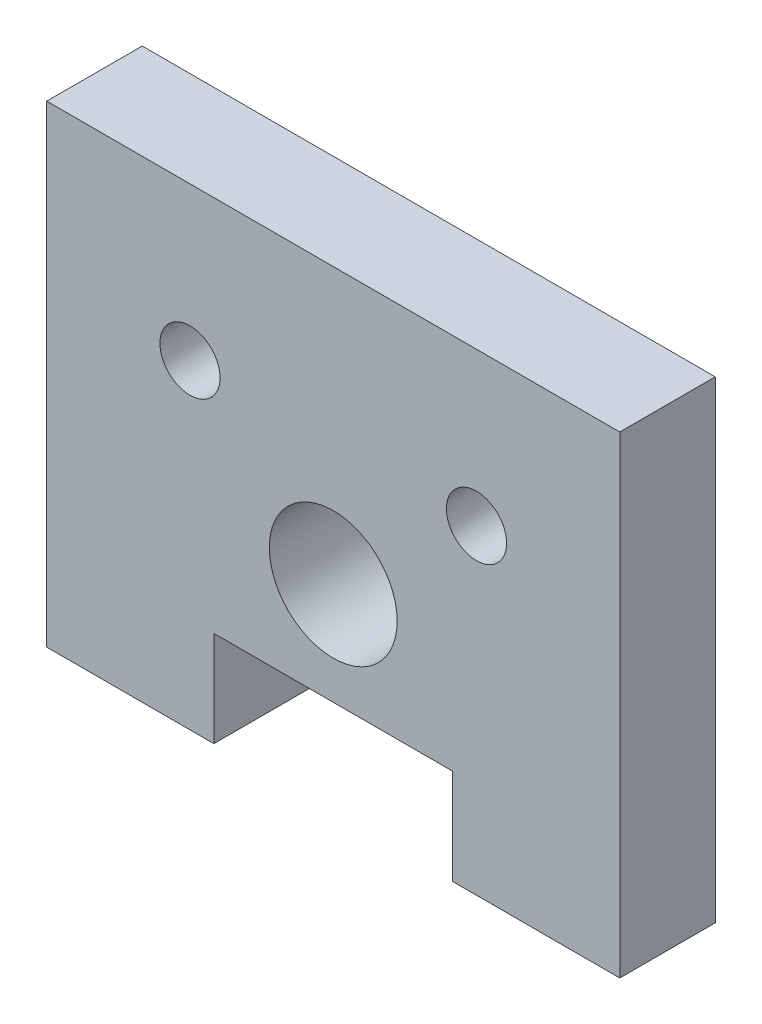
SolidWorks part; units mm, degrees
material "Acrylic (Medium-high impact)"
ref_plane "Front Plane" through (0, 0, 0) normal (0, 0, 1) x (1, 0, 0)
ref_plane "Top Plane" through (0, 0, 0) normal (0, 1, 0) x (1, 0, 0)
ref_plane "Right Plane" through (0, 0, 0) normal (1, 0, 0) x (0, 0, -1)
sketch "Sketch1" plane through (0, 0, 0) normal (0, 0, 1) x (1, 0, 0)
  line L0 (-15.875, -34.544) -> (-15.875, -21.844)
  line L1 (38.1, -34.544) -> (15.875, -34.544)
  line L2 (38.1, -34.544) -> (38.1, 34.544)
  line L4 (-38.1, -34.544) -> (-38.1, 34.544)
  line L5 (-15.875, -21.844) -> (15.875, -21.844)
  line L6 (15.875, -21.844) -> (15.875, -34.544)
  line L7 (-15.875, -34.544) -> (-38.1, -34.544)
  line L8 (0, -21.844) -> (0, -16.764)
  line L9 (-19.05, 28.3364) -> (-38.1, 28.3364)
  line L10 (-19.05, 28.3364) -> (38.1, 28.3364)
  circle A3 centre (0, -8.264) radius 8.5
  circle A4 centre (-19.05, 7.992) radius 4
  circle A5 centre (19.05, 7.992) radius 4
  point P0 (0, 0)
  point P6 (-38.1, 0)
  point P18 (0, -21.844)
  dimension "D3" = 17
  dimension "D5" = 8
  dimension "D8" = 31.75
  dimension "D9" = 12.7
  dimension "D10" = 5.08
  dimension "D4" = 16.256
  dimension "D6" = 19.05
  dimension "D7" = 19.05
  dimension "D2" = 76.2
extrude "Boss-Extrude1" add sketch "Sketch1" along normal blind 12.7
equation "\"D7@Sketch1\"=\"D6@Sketch1\""
